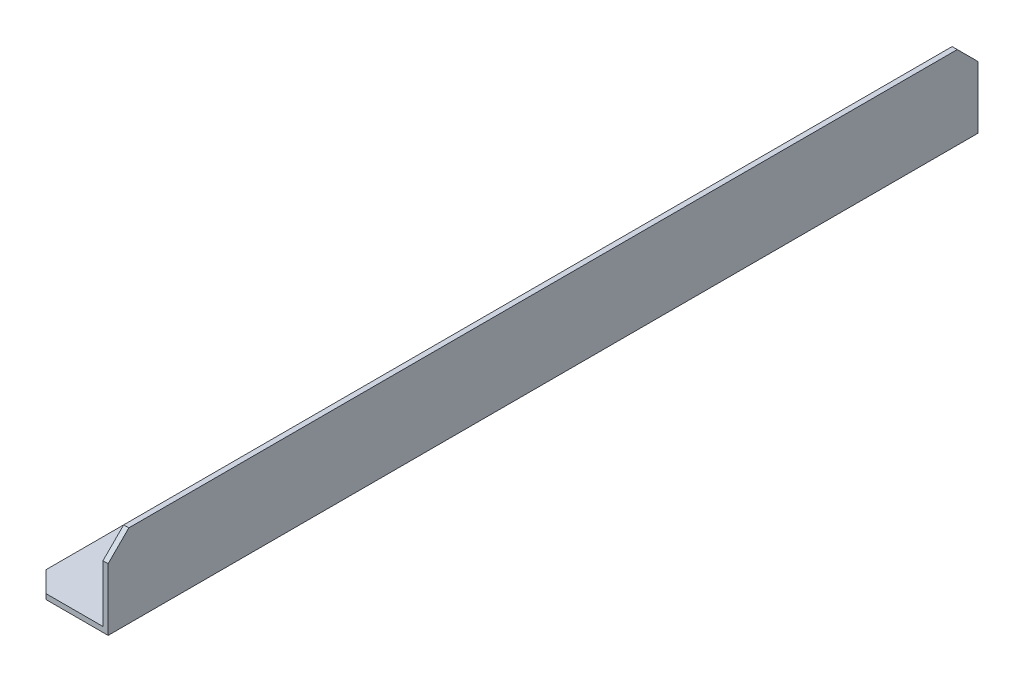
SolidWorks part; units mm, degrees
material "6063-T5"
ref_plane "Front Plane" through (0, 0, 0) normal (0, 0, 1) x (1, 0, 0)
ref_plane "Top Plane" through (0, 0, 0) normal (0, 1, 0) x (1, 0, 0)
ref_plane "Right Plane" through (0, 0, 0) normal (1, 0, 0) x (0, 0, -1)
sketch "Sketch2" plane through (0, 0, 0) normal (0, 0, 1) x (1, 0, 0)
  line L0 (0, 0) -> (0, 50.8)
  line L1 (0, 0) -> (-50.8, 0)
  line L2 (-3.175, 3.175) -> (-3.175, 50.8)
  line L3 (-3.175, 3.175) -> (-50.8, 3.175)
  line L4 (0, 50.8) -> (-3.175, 50.8)
  line L5 (-50.8, 0) -> (-50.8, 3.175)
  dimension "D1" = 50.8
  dimension "D2" = 50.8
  dimension "D3" = 3.175
extrude "Boss-Extrude1" add sketch "Sketch2" against normal blind 533.4
chamfer "Chamfer1" distance 12.7 angle 45 4 edges at (-50.8, 1.5875, -533.4) (-1.5875, 50.8, -533.4) (-1.5875, 50.8, 0) (-50.8, 1.5875, 0)
hole_wizard "CSK for #8 Flat Head Machine Screw (100)1" positions "Sketch3" profile "Sketch4" countersink size "#8" standard "ANSI Inch" end condition through all
sketch "Sketch3" plane through (0, 3.175, 0) normal (0, 1, 0) x (1, 0, 0)
  line L0 (-50.8, 266.7) -> (-3.175, 266.7) construction
  line L1 (-50.8, 520.7) -> (-50.8, 12.7) construction
  line L2 (-3.175, 533.4) -> (-3.175, 0) construction
  line L4 (-26.9875, 266.7) -> (-26.9875, 0) construction
  line L5 (-3.175, 0) -> (-38.1, 0) construction
  point P15 (-26.9875, 38.1)
  point P26 (-26.9875, 152.4)
  point P27 (-26.9875, 266.7)
  point P28 (-26.9875, 381)
  point P29 (-26.9875, 495.3)
  dimension "D3" = 114.3
  dimension "D2" = 5
sketch "Sketch4" plane through (-26.9875, 3.175, -495.3) normal (1, 0, 0) x (0, 0, 1)
  line L0 (0, 0) -> (0, 3.175)
  line L1 (0, 3.175) -> (2.4574, 3.175)
  line L2 (2.4574, 3.175) -> (2.4574, 1.4759)
  line L3 (2.4574, 1.4759) -> (4.2164, 0)
  line L5 (4.2164, 0) -> (0, 0)
  line L6 (-2.4574, 1.4759) -> (-4.2164, 0) construction
  line L11 (0, -6.35) -> (0, 107.95) construction
  dimension "Thru Hole Dia." = 4.9149
  dimension "Thru Hole Depth" = 3.175
  dimension "Near C'Sink Dia." = 8.4328
  dimension "Near C'Sink Angle" = 100
equation "\"D2@Sketch2\"=\"D1@Sketch2\""
